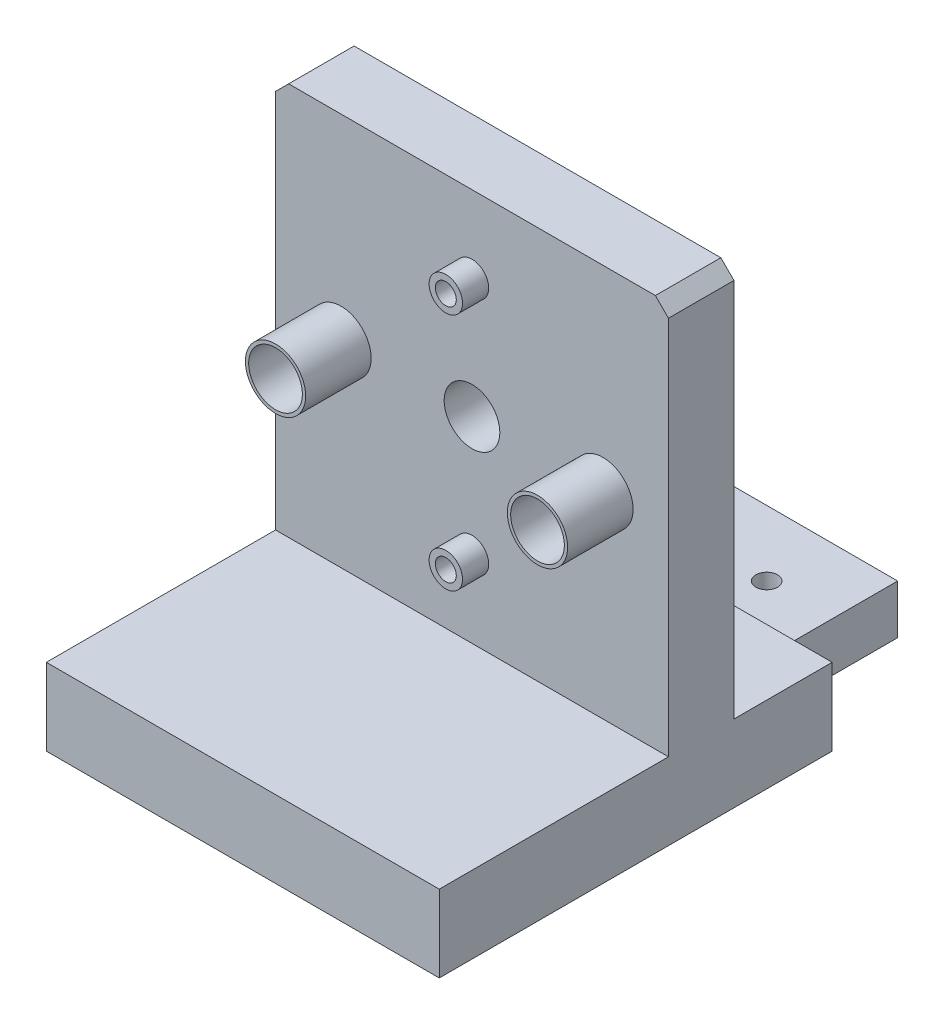
SolidWorks part; units mm, degrees
ref_plane "前视基准面" through (0, 0, 0) normal (0, 0, 1) x (1, 0, 0)
ref_plane "上视基准面" through (0, 0, 0) normal (0, 1, 0) x (1, 0, 0)
ref_plane "右视基准面" through (0, 0, 0) normal (1, 0, 0) x (0, 0, -1)
other "Configuration Table"
sketch "草图1" plane through (0, 0, 0) normal (0, 0, 1) x (1, 0, 0)
  line L1 (-30, -30) -> (30, -30)
  line L2 (-30, -30) -> (-30, 30)
  line L3 (-30, 30) -> (30, 30)
  line L4 (30, -30) -> (30, 30)
  line L5 (-30, -30) -> (30, 30) construction
  line L6 (-30, 30) -> (30, -30) construction
  point P0 (0, 0)
  dimension "D1" = 60
  dimension "D2" = 60
extrude "凸台-拉伸1" add sketch "草图1" along normal blind 10
hole_wizard "孔1" positions "草图2" profile "草图3" legacy
sketch "草图2" plane through (0, 0, 10) normal (0, 0, 1) x (1, 0, 0)
  point P0 (0, 0)
sketch "草图3" plane through (0, 0, 10) normal (1, 0, 0) x (0, -1, 0)
  line L0 (0, 0) -> (0, 20)
  line L1 (0, 20) -> (4.25, 20)
  line L2 (4.25, 20) -> (4.25, 0)
  line L3 (4.25, 0) -> (0, 0)
  line L4 (0, 110) -> (0, -10) construction
  dimension "直径" = 8.5
  dimension "深度" = 20
hole_wizard "孔2" positions "草图4" profile "草图5" legacy end condition through all
sketch "草图4" plane through (0, 0, 10) normal (0, 0, 1) x (1, 0, 0)
  point P0 (20, 0)
  point P2 (-20, 0)
  dimension "D1" = 20
  dimension "D2" = 20
sketch "草图5" plane through (20, 0, 10) normal (1, 0, 0) x (0, -1, 0)
  line L0 (0, 0) -> (0, 10)
  line L1 (0, 10) -> (4, 10)
  line L2 (4, 10) -> (4, 0.2414)
  line L3 (4, 0.2414) -> (4.1, 0)
  line L4 (4.1, 0) -> (0, 0)
  line L5 (0, -6.4453) -> (0, 115.525) construction
  line L6 (-4, 0.2414) -> (-4.1, 0) construction
  dimension "直径" = 8
  dimension "深度" = 10
  dimension "锥坑角度" = 45
  dimension "锥坑直径" = 8.2
hole_wizard "孔3" positions "草图6" profile "草图7" legacy end condition through all
sketch "草图6" plane through (0, 0, 0) normal (0, 0, -1) x (-1, 0, 0)
  point P0 (0, 18.25)
  point P2 (0, -18.25)
  dimension "D1" = 18.25
  dimension "D2" = 18.25
sketch "草图7" plane through (0, 18.25, 0) normal (1, 0, 0) x (0, 1, 0)
  line L0 (0, 0) -> (0, 10)
  line L1 (0, 10) -> (1.6, 10)
  line L2 (1.6, 10) -> (1.6, 0)
  line L3 (1.6, 0) -> (0, 0)
  line L4 (0, 110) -> (0, -10) construction
  dimension "直径" = 3.2
  dimension "深度" = 10
sketch "草图8" plane through (0, 0, 10) normal (0, 0, 1) x (1, 0, 0)
  circle A0 centre (-20, 0) radius 4.1
  circle A1 centre (-20, 0) radius 4.6
  dimension "D1" = 8.2
  dimension "D2" = 9.2
extrude "凸台-拉伸2" add sketch "草图8" along normal blind 10
ref_plane "基准面1" through (0, 0, 0) normal (1, 0, 0) x (0, 0, -1)
mirror "镜向1" about plane through (0, 0, 0) normal (1, 0, 0) of "凸台-拉伸2"
sketch "草图10" plane through (0, 0, 10) normal (0, 0, 1) x (1, 0, 0)
  circle A0 centre (0, 18.25) radius 1.6
  circle A1 centre (0, 18.25) radius 2.55
  dimension "D1" = 3.2
  dimension "D2" = 5.1
extrude "凸台-拉伸4" add sketch "草图10" along normal blind 4
ref_plane "基准面4" through (0, 0, 0) normal (0, 1, 0) x (1, 0, 0)
mirror "镜向4" about plane through (0, 0, 0) normal (0, 1, 0) of "凸台-拉伸4"
sketch "草图11" plane through (0, -30, 0) normal (0, -1, 0) x (1, 0, 0)
  line L0 (0, -33) -> (0, 33) construction
  line L1 (-30, -35) -> (30, -35)
  line L2 (-30, -35) -> (-30, 45)
  line L3 (-30, 45) -> (30, 45)
  line L4 (30, -35) -> (30, 45)
  line L5 (-30, -35) -> (30, 45) construction
  line L6 (-30, 45) -> (30, -35) construction
  point P0 (0, 5)
  dimension "D1" = 60
  dimension "D2" = 80
extrude "凸台-拉伸5" add sketch "草图11" along normal blind 11.75
sketch "草图12" plane through (0, -41.75, 0) normal (0, -1, 0) x (1, 0, 0)
  line L4 (-20, -35) -> (-20, -15)
  line L5 (0, -5.5) -> (0, 5.5) construction
  line L6 (20, -35) -> (20, -15)
  line L7 (-20, -15) -> (-30, -15)
  line L8 (-30, 45) -> (-30, -35) construction
  line L9 (20, -15) -> (30, -15)
  line L10 (30, -35) -> (30, 45) construction
  line L11 (-30, -15) -> (-30, -35)
  line L12 (-30, -35) -> (-20, -35)
  line L13 (20, -35) -> (30, -35)
  line L14 (-30, -35) -> (30, -35) construction
  line L15 (30, -35) -> (30, -15)
  dimension "D2" = 20
extrude "切除-拉伸3" cut sketch "草图12" against normal through all
sketch "草图13" plane through (0, -30, 0) normal (0, 1, 0) x (1, 0, 0)
  line L1 (-20, 35) -> (20, 35)
  line L2 (-20, 35) -> (-20, 15)
  line L3 (-20, 15) -> (20, 15)
  line L4 (20, 35) -> (20, 15)
extrude "切除-拉伸4" cut sketch "草图13" against normal blind 4.25
hole_wizard "孔4" positions "草图14" profile "草图15" legacy end condition through all
sketch "草图14" plane through (0, -41.75, 0) normal (0, -1, 0) x (-1, 0, 0)
  point P0 (-10, 25)
  point P3 (10, 25)
sketch "草图15" plane through (10, -41.75, -25) normal (1, 0, 0) x (0, 0, -1)
  line L0 (0, 0) -> (0, 71.75)
  line L1 (0, 71.75) -> (1.65, 71.75)
  line L2 (1.65, 71.75) -> (1.65, 0)
  line L3 (1.65, 0) -> (0, 0)
  line L4 (0, 110) -> (0, -10) construction
  dimension "直径" = 3.3
  dimension "深度" = 71.75
chamfer "倒角1" distance 2 angle 45 2 edges at (-30, 30, 5) (30, 30, 5)
